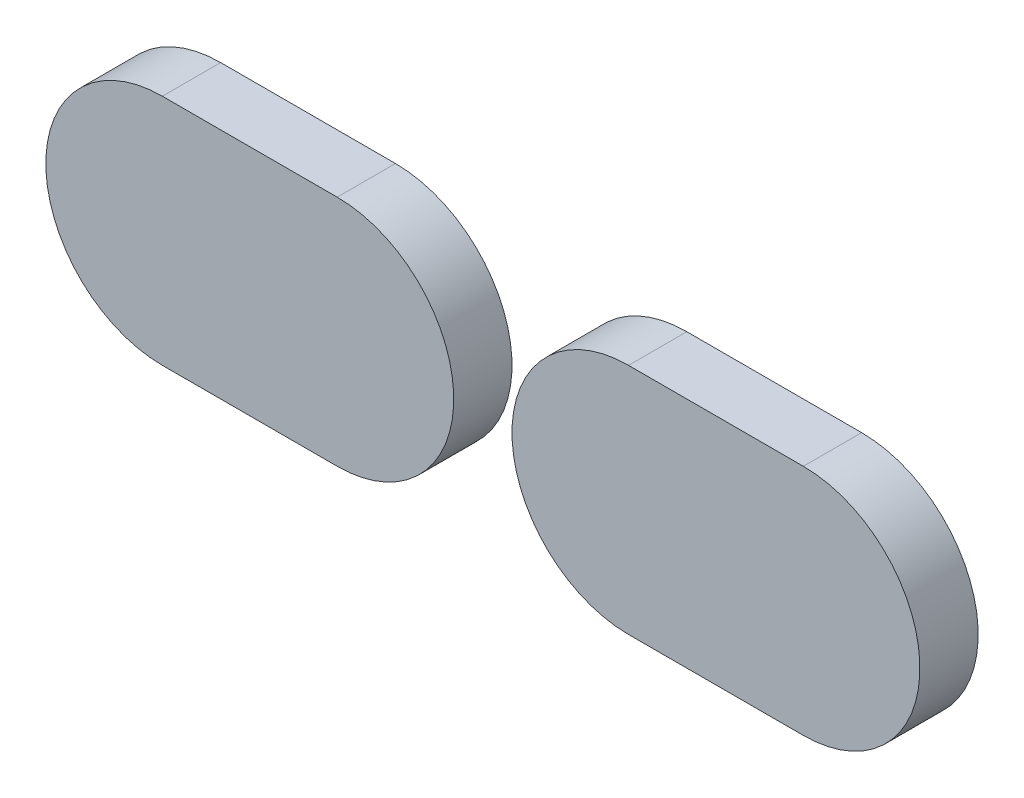
SolidWorks part; units mm, degrees
ref_plane "Plan de face" through (0, 0, 0) normal (0, 0, 1) x (1, 0, 0)
ref_plane "Plan de dessus" through (0, 0, 0) normal (0, 1, 0) x (1, 0, 0)
ref_plane "Plan de droite" through (0, 0, 0) normal (1, 0, 0) x (0, 0, -1)
sketch "Esquisse1" plane through (0, 0, 0) normal (0, 0, 1) x (1, 0, 0)
  line L0 (0, 0) -> (30, 0) construction
  line L1 (0, 20) -> (30, 20)
  line L2 (0, -20) -> (30, -20)
  line L3 (80, 0) -> (110, 0) construction
  line L4 (80, 20) -> (110, 20)
  line L5 (80, -20) -> (110, -20)
  arc A0 (0, 20) -> (0, -20) centre (0, 0) ccw
  arc A1 (30, -20) -> (30, 20) centre (30, 0) ccw
  arc A2 (80, 20) -> (80, -20) centre (80, 0) ccw
  arc A3 (110, -20) -> (110, 20) centre (110, 0) ccw
  point P3 (15, 0)
  point P8 (95, 0)
  dimension "D4" = 20
  dimension "D1" = 30
  dimension "D2" = 30
  dimension "D3" = 110
extrude "Boss.-Extru.1" add sketch "Esquisse1" along normal blind 10
